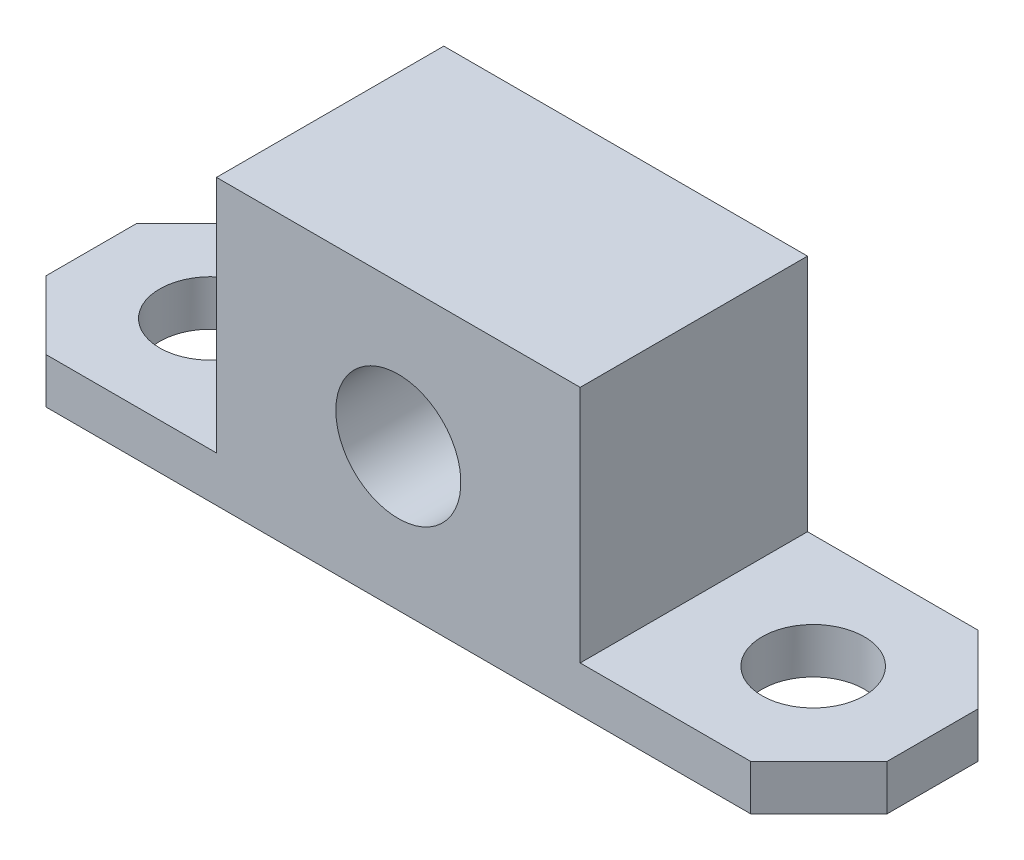
SolidWorks part; units mm, degrees
ref_plane "Front Plane" through (0, 0, 0) normal (0, 0, 1) x (1, 0, 0)
ref_plane "Top Plane" through (0, 0, 0) normal (0, 1, 0) x (1, 0, 0)
ref_plane "Right Plane" through (0, 0, 0) normal (1, 0, 0) x (0, 0, -1)
sketch "Sketch1" plane through (0, 0, 0) normal (0, 1, 0) x (1, 0, 0)
  line L1 (0, 0) -> (37, 0)
  line L2 (0, 0) -> (0, 10)
  line L3 (0, 10) -> (37, 10)
  line L4 (37, 0) -> (37, 10)
  dimension "D1" = 10
  dimension "D2" = 37
extrude "Boss-Extrude1" add sketch "Sketch1" along normal blind 2
sketch "Sketch2" plane through (0, 2, 0) normal (0, 1, 0) x (1, 0, 0)
  line L0 (18.5, 10) -> (18.5, 0) construction
  line L1 (37, 10) -> (0, 10) construction
  line L2 (0, 0) -> (37, 0) construction
  line L4 (10.5, 0) -> (26.5, 0)
  line L5 (10.5, 0) -> (10.5, 10)
  line L6 (10.5, 10) -> (26.5, 10)
  line L7 (26.5, 0) -> (26.5, 10)
  line L8 (10.5, 0) -> (26.5, 10) construction
  line L9 (10.5, 10) -> (26.5, 0) construction
  point P6 (18.5, 5)
  dimension "D1" = 16
extrude "Boss-Extrude2" add sketch "Sketch2" along normal blind 10.5
sketch "Sketch3" plane through (0, 0, -10) normal (0, 0, -1) x (-1, 0, 0)
  line L0 (-26.5, 2) -> (-26.5, 0) construction
  line L1 (-37, 0) -> (0, 0) construction
  line L2 (-26.5, 0) -> (-10.5, 12.5) construction
  circle A0 centre (-18.5, 6.25) radius 2.75
  point P9 (0, 0)
  point P12 (-18.5, 6.25)
  dimension "D1" = 5.5
extrude "Cut-Extrude1" cut sketch "Sketch3" against normal through all
sketch "Sketch4" plane through (0, 2, 0) normal (0, 1, 0) x (1, 0, 0)
  line L0 (0, 10) -> (10.5, 0) construction
  line L1 (10.5, 0) -> (26.5, 0) construction
  line L2 (26.5, 0) -> (37, 10) construction
  circle A0 centre (5.25, 5) radius 2.25
  circle A1 centre (31.75, 5) radius 2.25
  dimension "D1" = 4.5
  dimension "D2" = 4.5
extrude "Cut-Extrude2" cut sketch "Sketch4" against normal blind 10
chamfer "Chamfer1" distance 3 angle 45 4 edges at (0, 1, -10) (0, 1, 0) (37, 1, 0) (37, 1, -10)
